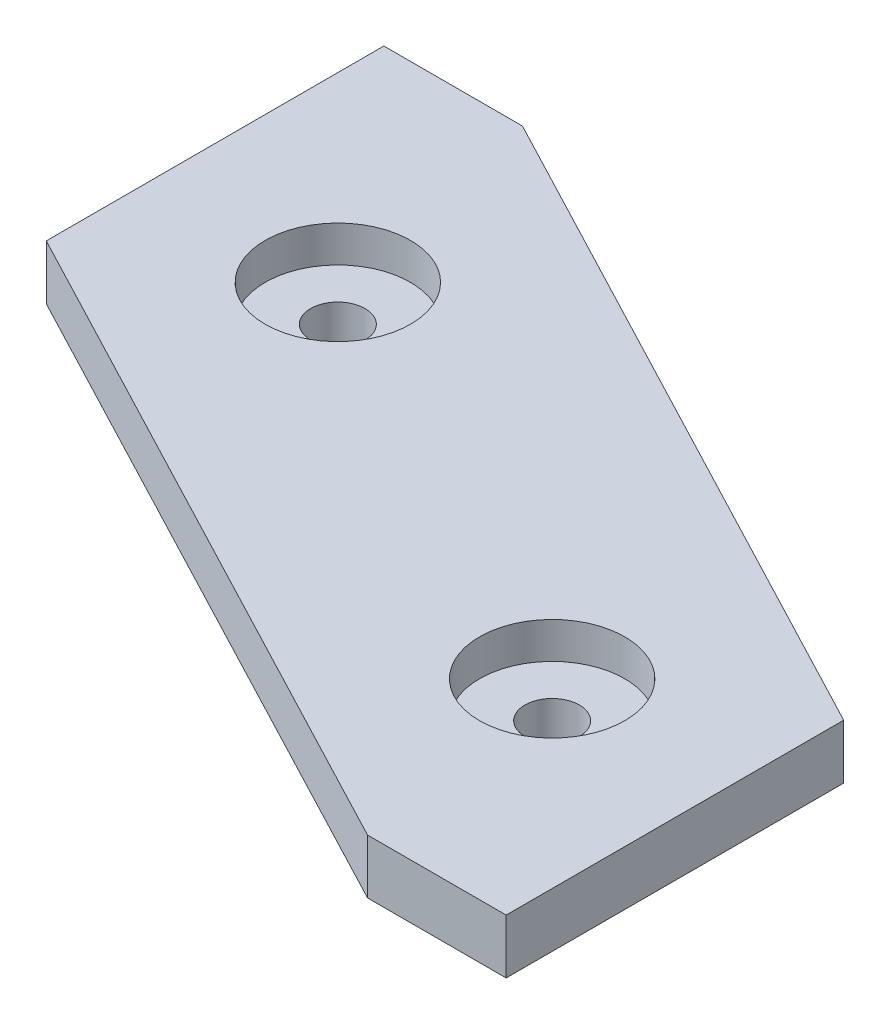
SolidWorks part; units mm, degrees
ref_plane "Front Plane" through (0, 0, 0) normal (0, 0, 1) x (1, 0, 0)
ref_plane "Top Plane" through (0, 0, 0) normal (0, 1, 0) x (1, 0, 0)
ref_plane "Right Plane" through (0, 0, 0) normal (1, 0, 0) x (0, 0, -1)
sketch "Sketch1" plane through (0, 0, 0) normal (0, 1, 0) x (1, 0, 0)
  line L0 (0, 6) -> (0, -19) construction
  line L1 (0, -19) -> (24.7992, -19) construction
  circle A0 centre (0, 0) radius 6
  circle A1 centre (24.7992, -13) radius 6
  dimension "D1" = 28
  dimension "D2" = 12
  dimension "D3" = 12
  dimension "D4" = 25
sketch "Sketch3" plane through (0, 0, 0) normal (0, 1, 0) x (1, 0, 0)
  line L0 (-10, 16.5328) -> (-10, -6.0486)
  line L1 (-10, -6.0486) -> (34.7992, -29.5328)
  line L2 (34.7992, -29.5328) -> (34.7992, -6.9514)
  line L3 (34.7992, -6.9514) -> (-10, 16.5328)
  line L5 (0, 0) -> (24.7992, -13) construction
  line L6 (0, 6) -> (0, -19) construction
  dimension "D1" = 10
  dimension "D2" = 10
  dimension "D3" = 10
  dimension "D4" = 10
extrude "Boss-Extrude1" add sketch "Sketch3" along normal blind 3
extrude "Boss-Extrude3" add sketch "Sketch1" against normal blind 2
sketch "Sketch4" plane through (0, 3, 0) normal (0, 1, 0) x (1, 0, 0)
  circle A0 centre (0, 0) radius 1.5
  circle A1 centre (24.7992, -13) radius 1.5
  dimension "D1" = 3
  dimension "D2" = 3
extrude "Cut-Extrude1" cut sketch "Sketch4" against normal through all
sketch "Sketch5" plane through (0, 3, 0) normal (0, 1, 0) x (1, 0, 0)
  circle A0 centre (0, 0) radius 4
  circle A1 centre (24.7992, -13) radius 4
  dimension "D1" = 8
  dimension "D2" = 8
extrude "Cut-Extrude2" cut sketch "Sketch5" against normal blind 2
sketch "Sketch7" plane through (0, 3, 0) normal (0, 1, 0) x (1, 0, 0)
  line L0 (-10, 16.5328) -> (-10, 12.5328)
  line L1 (-10, 16.5328) -> (-10, -6.0486) construction
  line L2 (-10, 12.5328) -> (-2.3695, 12.5328)
  line L3 (34.7992, -6.9514) -> (-10, 16.5328) construction
  line L4 (-2.3695, 12.5328) -> (-10, 16.5328)
  line L5 (34.7992, -29.5328) -> (34.7992, -25.5328)
  line L6 (34.7992, -29.5328) -> (34.7992, -6.9514) construction
  line L7 (34.7992, -25.5328) -> (27.1687, -25.5328)
  line L8 (-10, -6.0486) -> (34.7992, -29.5328) construction
  line L9 (27.1687, -25.5328) -> (34.7992, -29.5328)
  dimension "D1" = 4
extrude "Cut-Extrude3" cut sketch "Sketch7" against normal through all
